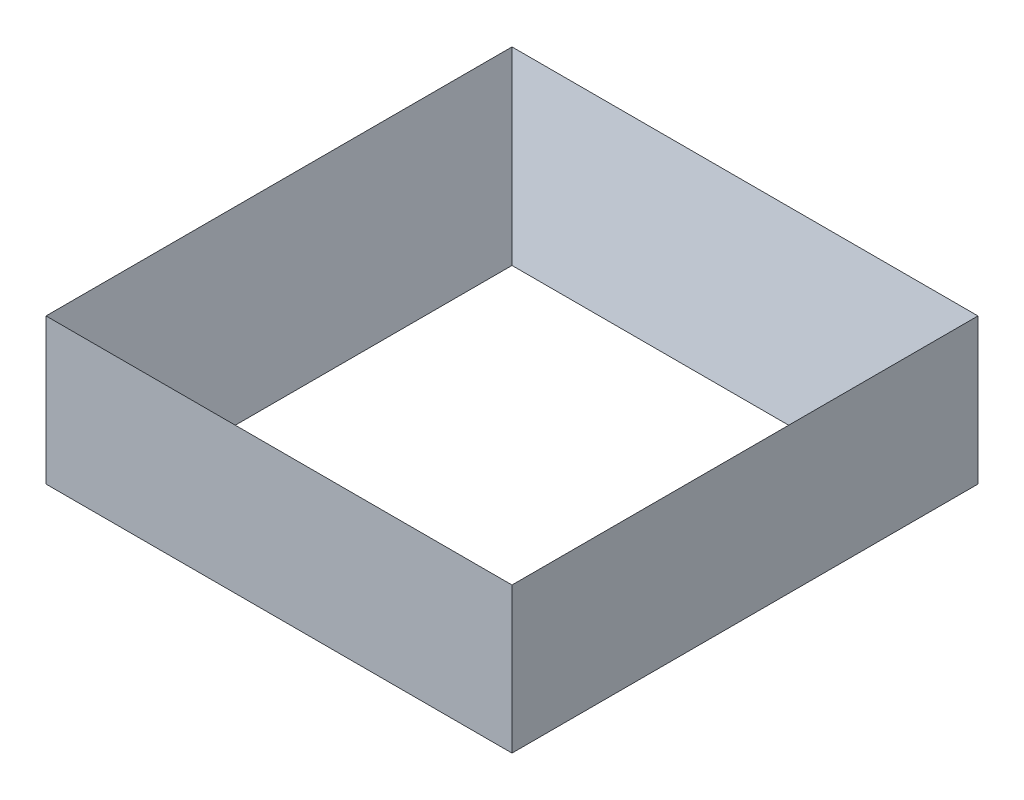
SolidWorks part; units mm, degrees
ref_plane "前视基准面" through (0, 0, 0) normal (0, 0, 1) x (1, 0, 0)
ref_plane "上视基准面" through (0, 0, 0) normal (0, 1, 0) x (1, 0, 0)
ref_plane "右视基准面" through (0, 0, 0) normal (1, 0, 0) x (0, 0, -1)
sketch "草图1" plane through (0, 0, 0) normal (0, 1, 0) x (1, 0, 0)
  line L1 (0, 0) -> (64, 0)
  line L2 (0, 0) -> (0, 64)
  line L3 (0, 64) -> (64, 64)
  line L4 (64, 0) -> (64, 64)
extrude "凸台-拉伸1" add sketch "草图1" along normal blind 20
sketch "草图2" plane through (0, 20, 0) normal (0, 1, 0) x (1, 0, 0)
  line L4 (0, 64) -> (0, 0)
  line L5 (0, 0) -> (64, 0)
  line L6 (64, 0) -> (64, 64)
  line L7 (64, 64) -> (0, 64)
  line L8 (0, 64) -> (0, 0)
  line L9 (0, 0) -> (64, 0)
  line L10 (64, 0) -> (64, 64)
  line L11 (64, 64) -> (0, 64)
  dimension "D1" = 0
sketch "草图3" plane through (0, 0, 0) normal (0, -1, 0) x (1, 0, 0)
  line L1 (6, -6) -> (58, -6)
  line L2 (6, -6) -> (6, -58)
  line L3 (6, -58) -> (58, -58)
  line L4 (58, -6) -> (58, -58)
loft "切除-放样1" cut profiles "草图3", "草图2"
